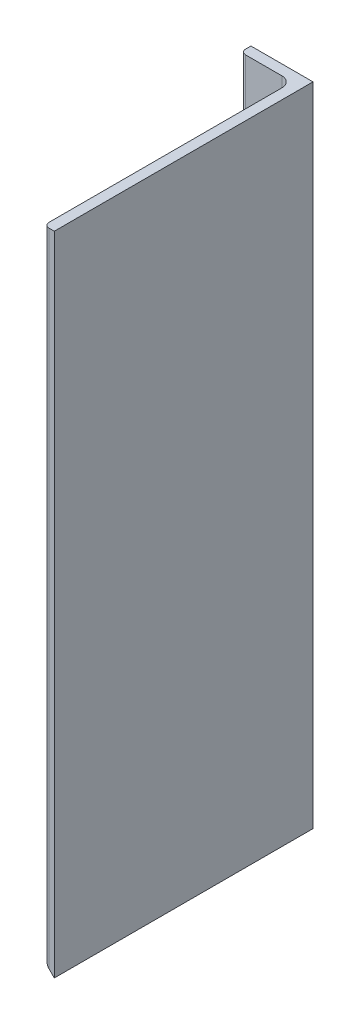
SolidWorks part; units mm, degrees
ref_plane "Front Plane" through (0, 0, 0) normal (0, 0, 1) x (1, 0, 0)
ref_plane "Top Plane" through (0, 0, 0) normal (0, 1, 0) x (1, 0, 0)
ref_plane "Right Plane" through (0, 0, 0) normal (1, 0, 0) x (0, 0, -1)
sketch "Sketch2" plane through (0, 0, 0) normal (0, 1, 0) x (1, 0, 0)
  line L0 (174.6287, -52.4983) -> (174.6287, -2.4983)
  line L1 (174.6287, -2.4983) -> (162.6287, -2.4983)
  line L2 (162.6287, -2.4983) -> (162.6287, -4.4983)
  line L3 (162.6287, -4.4983) -> (172.6287, -4.4983)
  line L4 (172.6287, -4.4983) -> (172.6287, -52.4983)
  line L5 (172.6287, -52.4983) -> (174.6287, -52.4983)
  dimension "D1" = 2
  dimension "D2" = 50
  dimension "D3" = 2
  dimension "D4" = 12
extrude "Boss-Extrude1" add sketch "Sketch2" along normal blind 125
fillet "Fillet1" radius 1 2 edges at (162.6287, 62.5, 4.4983) (172.6287, 62.5, 52.4983)
fillet "Fillet2" radius 2 1 edges at (172.6287, 62.5, 4.4983)
sketch "Sketch3" plane through (0, 0, 4.4983) normal (0, 0, 1) x (1, 0, 0)
  line L0 (163.6287, 125) -> (170.6287, 125) construction
  line L1 (162.6287, 0) -> (162.6287, 125) construction
  line L2 (163.6287, 0) -> (170.6287, 0) construction
  circle A0 centre (167.1287, 20) radius 1.6
  circle A1 centre (167.1287, 105) radius 1.6
  dimension "D1" = 3.2
  dimension "D2" = 3.2
  dimension "D3" = 20
  dimension "D4" = 4.5
  dimension "D5" = 20
  dimension "D6" = 4.5
extrude "Cut-Extrude1" cut sketch "Sketch3" against normal through all
sketch "Sketch4" plane through (0, 0, 4.4983) normal (0, 0, 1) x (1, 0, 0)
  line L0 (174.6287, 0) -> (162.6287, 12)
  line L1 (162.6287, 0) -> (162.6287, 125) construction
  line L2 (162.6287, 12) -> (162.6287, 0)
  line L3 (162.6287, 0) -> (174.6287, 0)
extrude "Cut-Extrude2" cut sketch "Sketch4" against normal through all both and the other way through all
